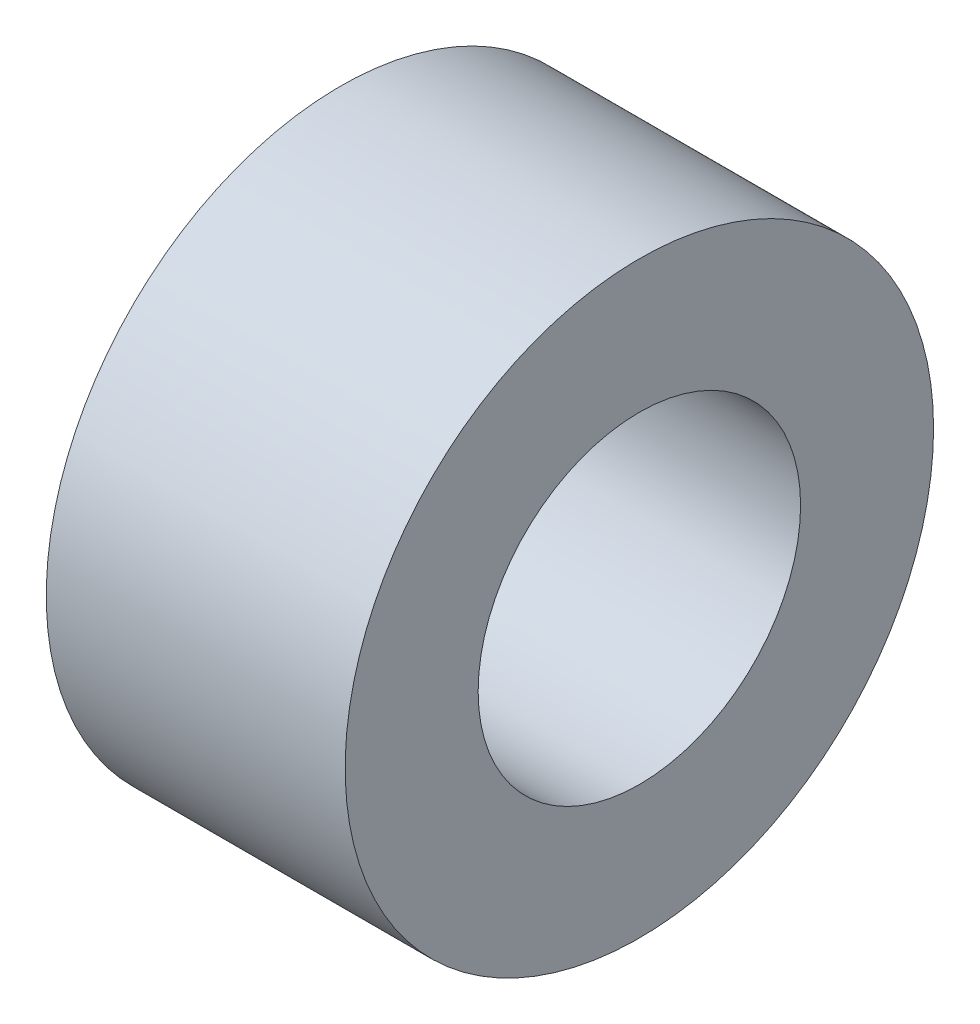
SolidWorks part; units mm, degrees
material "CMR DEFAULT - CHANGE MATERIAL"
ref_plane "XY PLANE - TOP" through (0, 0, 0) normal (0, 0, 1) x (1, 0, 0)
ref_plane "XZ PLANE - SIDE" through (0, 0, 0) normal (0, 1, 0) x (1, 0, 0)
ref_plane "YZ PLANE - FRONT" through (0, 0, 0) normal (1, 0, 0) x (0, 0, -1)
sketch "Sketch1" plane through (0, 0, 0) normal (1, 0, 0) x (0, 0, -1)
  circle A0 centre (0, 0) radius 6.25
  circle A1 centre (0, 0) radius 3.425
  dimension "D1" = 12.5
  dimension "D2" = 6.85
extrude "Boss-Extrude1" add sketch "Sketch1" along normal blind 6.35
